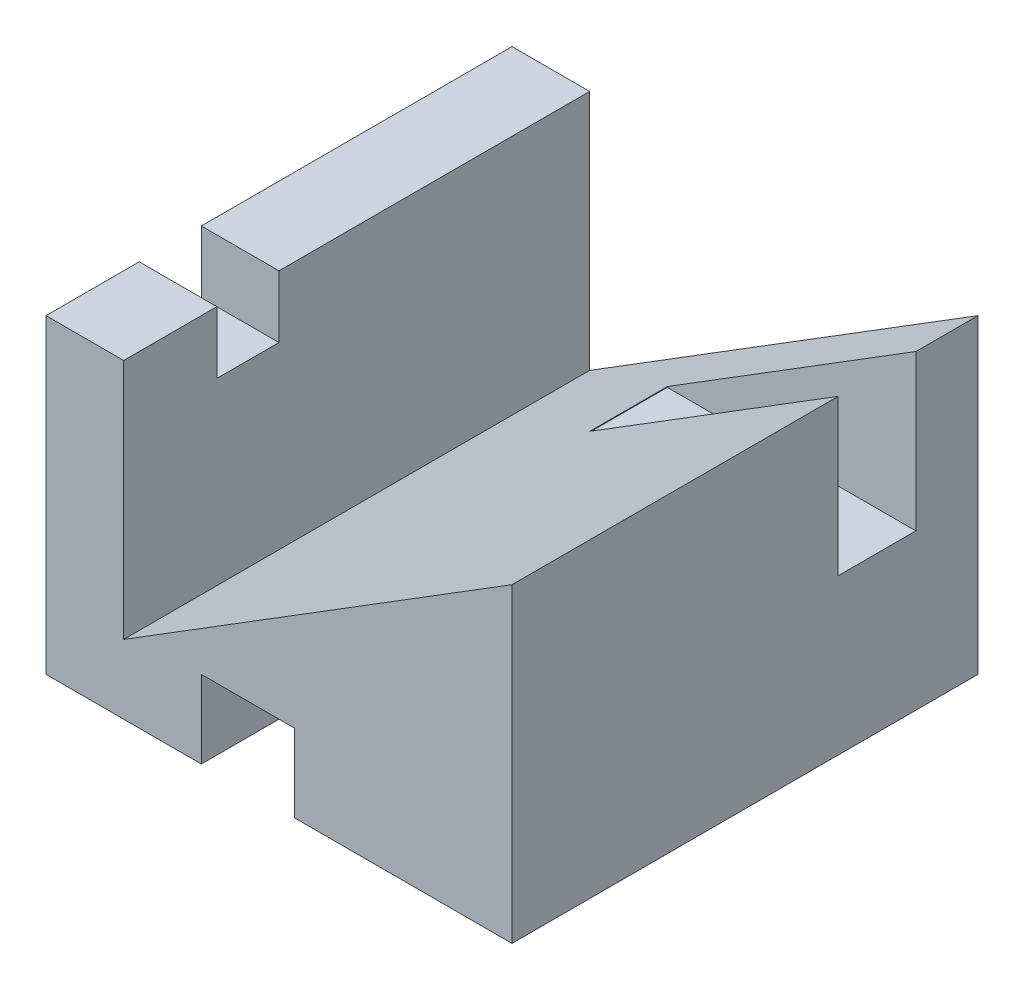
SolidWorks part; units mm, degrees
ref_plane "前基準面" through (0, 0, 0) normal (0, 0, 1) x (1, 0, 0)
ref_plane "上基準面" through (0, 0, 0) normal (0, 1, 0) x (1, 0, 0)
ref_plane "右基準面" through (0, 0, 0) normal (1, 0, 0) x (0, 0, -1)
sketch "草圖1" plane through (0, 0, 0) normal (0, 0, 1) x (1, 0, 0)
  line L1 (-15, 10) -> (15, 10)
  line L2 (-15, 10) -> (-15, -10)
  line L3 (-15, -10) -> (15, -10)
  line L4 (15, 10) -> (15, -10)
  line L5 (-15, 10) -> (15, -10) construction
  line L6 (-15, -10) -> (15, 10) construction
  point P0 (0, 0)
  dimension "D1" = 30
  dimension "D2" = 20
extrude "填料-伸長1" add sketch "草圖1" along normal blind 30
sketch "草圖2" plane through (0, 0, 30) normal (0, 0, 1) x (1, 0, 0)
  line L0 (-15, -10) -> (15, -10) construction
  line L1 (-5, -10) -> (1, -10)
  line L2 (-5, -10) -> (-5, -5)
  line L3 (-5, -5) -> (1, -5)
  line L4 (1, -10) -> (1, -5)
  line L5 (-15, 10) -> (-15, -10) construction
  dimension "D1" = 10
  dimension "D2" = 6
  dimension "D3" = 5
extrude "除料-伸長1" cut sketch "草圖2" against normal blind 30
sketch "草圖3" plane through (0, 0, 30) normal (0, 0, 1) x (1, 0, 0)
  line L0 (-10, 10) -> (-10, -5.5512)
  line L1 (15, 10) -> (-15, 10) construction
  line L2 (-10, -5.5512) -> (15, 10)
  line L3 (-10, 10) -> (15, 10)
  line L4 (-15, 10) -> (-15, -10) construction
  dimension "D1" = 5
extrude "除料-伸長2" cut sketch "草圖3" against normal blind 30
sketch "草圖4" plane through (0, 10, 0) normal (0, 1, 0) x (1, 0, 0)
  line L0 (-15, -30) -> (-15, 0) construction
  line L1 (-15, -20) -> (-10, -20)
  line L2 (-15, -20) -> (-15, -24)
  line L3 (-15, -24) -> (-10, -24)
  line L4 (-10, -20) -> (-10, -24)
  line L5 (-10, 0) -> (-10, -30) construction
  line L6 (-10, -30) -> (-15, -30) construction
  line L7 (-10, 0) -> (-15, 0) construction
  dimension "D1" = 5
  dimension "D2" = 6
  dimension "D3" = 20
extrude "除料-伸長3" cut sketch "草圖4" against normal blind 4
sketch "草圖6" plane through (0, 10, 0) normal (0, 1, 0) x (1, 0, 0)
  line L0 (15, -30) -> (15, 0) construction
  line L1 (15, -4) -> (-1, -4)
  line L2 (15, -4) -> (15, -9)
  line L3 (15, -9) -> (-1, -9)
  line L4 (-1, -4) -> (-1, -9)
  line L5 (-10, 0) -> (15, 0) construction
  dimension "D1" = 16
  dimension "D2" = 5
  dimension "D3" = 4
extrude "除料-伸長4" cut sketch "草圖6" against normal blind 10
